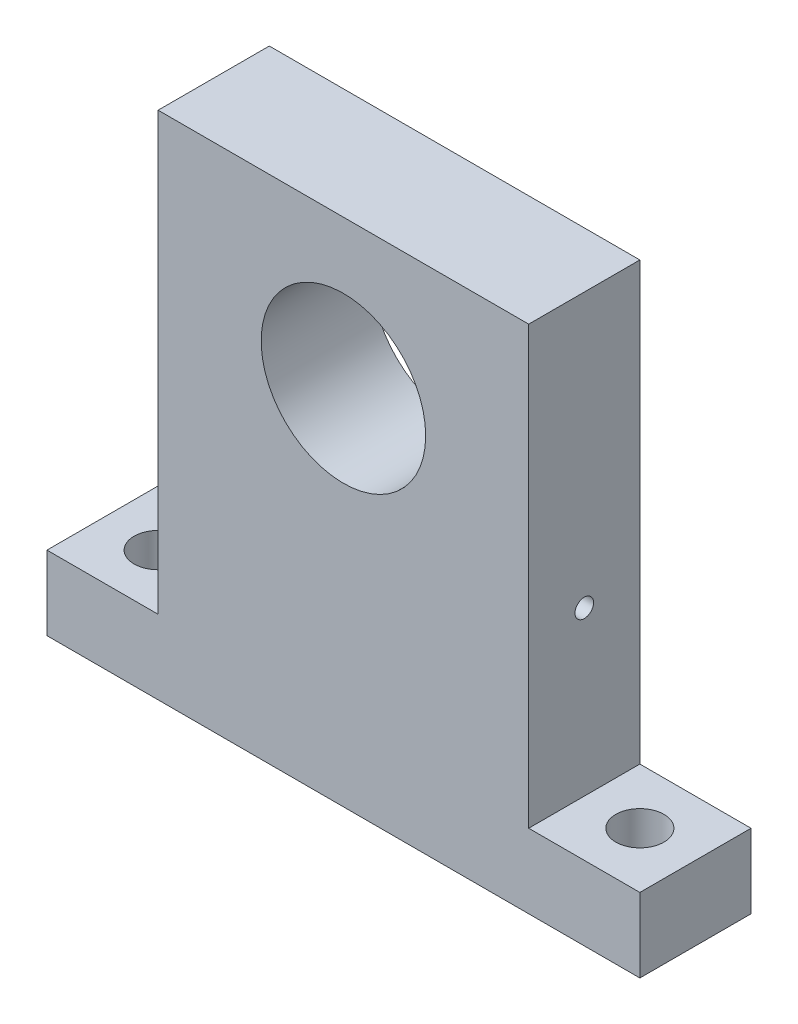
SolidWorks part; units mm, degrees
material "6061-T6 (SS)"
ref_plane "Frontal Plane" through (0, 0, 0) normal (0, 0, 1) x (1, 0, 0)
ref_plane "Horizontal Plane" through (0, 0, 0) normal (0, 1, 0) x (1, 0, 0)
ref_plane "Profile Plane" through (0, 0, 0) normal (1, 0, 0) x (0, 0, -1)
sketch "Sketch1" plane through (0, 0, 0) normal (0, 0, 1) x (1, 0, 0)
  line L0 (-40, 0) -> (40, 0)
  line L1 (40, 0) -> (40, 10)
  line L2 (40, 10) -> (25, 10)
  line L3 (25, 10) -> (25, 68.9056)
  line L4 (25, 68.9056) -> (-25, 68.9056)
  line L5 (-25, 68.9056) -> (-25, 10)
  line L6 (-25, 10) -> (-40, 10)
  line L7 (-40, 10) -> (-40, 0)
  circle A0 centre (0, 48.9056) radius 11.0998
  point P4 (0, 0)
  dimension "D2" = 22.1996
  dimension "D1" = 48.9056
  dimension "D3" = 15
  dimension "D4" = 10
  dimension "D5" = 50
  dimension "D6" = 20
extrude "Boss-Extrude1" add sketch "Sketch1" along normal blind 15
sketch "Sketch2" plane through (0, 10, 0) normal (0, 1, 0) x (1, 0, 0)
  line L0 (-40, -15) -> (-40, 0) construction
  line L1 (40, -15) -> (40, 0) construction
  circle A0 centre (-32.5, -7.5) radius 3.25
  circle A1 centre (32.5, -7.5) radius 3.25
  point P10 (-40, -7.5)
  dimension "D1" = 6.5
  dimension "D2" = 7.5
  dimension "D3" = 7.5
extrude "Cut-Extrude1" cut sketch "Sketch2" against normal through all
sketch "Sketch3" plane through (25, 0, 0) normal (1, 0, 0) x (0, 0, -1)
  line L0 (-15, 0) -> (0, 0) construction
  circle A0 centre (-7.5, 32) radius 1.25
  point P5 (-7.5, 0)
  dimension "D1" = 2.5
  dimension "D2" = 32
extrude "Cut-Extrude2" cut sketch "Sketch3" against normal blind 4.5
equation "\"BaseL\"= 6ft"
equation "\"BaseW\"= 5.5in"
equation "\"BaseThickness\"= 1in"
equation "\"RailGap\"= 4cm"
equation "\"SlidePlateL\"= 8cm"
equation "\"SlidePlateW\"= 11cm"
equation "\"SlidePlateThickness\"= 5mm"
equation "\"SlidePlateClearance\"= 1cm"
equation "\"BoxThickness\"= .5cm"
equation "\"BoxX\"= \"RailGap\" + 30mm"
equation "\"BoxH\"= 2cm + \"SlidePlateClearance\" + \"SlidePlateThickness\" + 3cm"
equation "\"PulleyRadius\"= 15.1mm"
equation "\"PulleyH\"= 30mm + 21.4056mm - 2.5mm"
equation "\"PulleyShaftDiameter\"= .3125in"
equation "\"PulleyShaftL\"= 4in"
equation "\"PulleyShaft2L\"= 3in"
equation "\"MotorL\"= 4.43in"
equation "\"MotorRadius\"= 1.291in"
equation "\"MotorShaftRadius\"= .15625in"
equation "\"MotorShaftL\"= 1.75in"
equation "\"HeadstoneThickness\"= 7.5mm"
equation "\"BeltL\"= 1500mm + \"80\""
equation "\"BeltThickness\"= 2.5mm"
equation "\"BeltW\"= .375in"
equation "\"BeltLockH\"= \"PulleyH\" + 19.4056mm - (\"SlidePlateThickness\" + \"SlidePlateClearance\" + 15mm + 5mm)"
equation "\"EncoderL\"= 33mm"
equation "\"EncoderRadius\"= 19mm"
equation "\"EncoderShaftRadius\"= 3mm"
equation "\"EncoderShaftL\"= 15mm"
equation "\"PendulumShaftL\"= \"100mm\" "
equation "\"PendulumShaftRadius\"= 3mm"
equation "\"RodL\"= 39in"
equation "\"RodRadius\"= 3mm"
equation "\"PillowBlockCenterH\"= \"EncoderRadius\" + 2mm"
equation "\"D1@Sketch1\"=\"PulleyH\""
